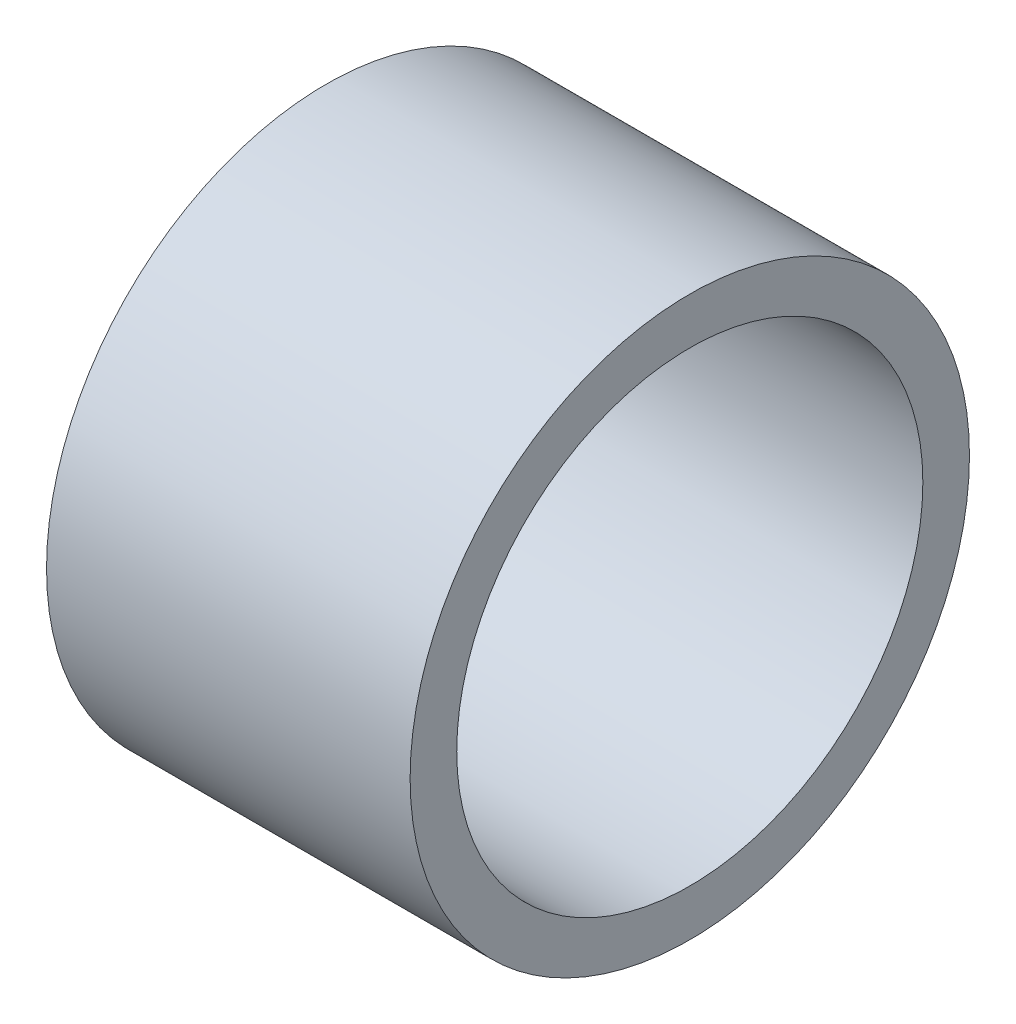
SolidWorks part; units mm, degrees
ref_plane "Front Plane" through (0, 0, 0) normal (0, 0, 1) x (1, 0, 0)
ref_plane "Top Plane" through (0, 0, 0) normal (0, 1, 0) x (1, 0, 0)
ref_plane "Right Plane" through (0, 0, 0) normal (1, 0, 0) x (0, 0, -1)
sketch "Sketch1" plane through (0, 0, 0) normal (1, 0, 0) x (0, 0, -1)
  circle A0 centre (0, 0) radius 5
  circle A1 centre (0, 0) radius 6
  dimension "D1" = 10
  dimension "D2" = 12
extrude "Boss-Extrude1" add sketch "Sketch1" along normal blind 7.8
